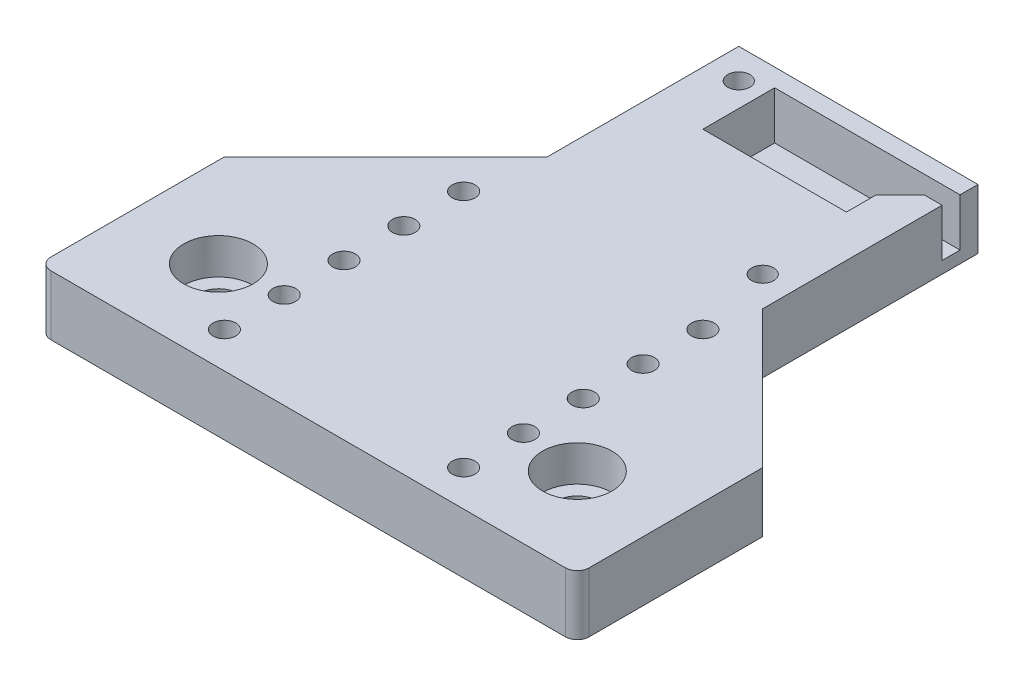
SolidWorks part; units mm, degrees
ref_plane "Front Plane" through (0, 0, 0) normal (0, 0, 1) x (1, 0, 0)
ref_plane "Top Plane" through (0, 0, 0) normal (0, 1, 0) x (1, 0, 0)
ref_plane "Right Plane" through (0, 0, 0) normal (1, 0, 0) x (0, 0, -1)
sketch "Sketch1" plane through (0, 0, 0) normal (0, 1, 0) x (1, 0, 0)
  line L0 (0, 0) -> (0, 22.5) construction
  line L1 (-22.5, -22.5) -> (22.5, -22.5)
  line L2 (-22.5, -22.5) -> (-22.5, 22.5)
  line L3 (-22.5, 22.5) -> (22.5, 22.5)
  line L4 (22.5, -22.5) -> (22.5, 22.5)
  line L5 (-22.5, -22.5) -> (22.5, 22.5) construction
  line L6 (-22.5, 22.5) -> (22.5, -22.5) construction
  line L7 (-15, 15) -> (-15, -15) construction
  line L8 (-15, 15) -> (15, 15) construction
  line L9 (0, 0) -> (-15, 0) construction
  circle A0 centre (-15, 15) radius 1.7
  circle A2 centre (-15, -15) radius 1.7
  circle A3 centre (15, -15) radius 1.7
  circle A5 centre (15, 15) radius 1.7
  point P0 (0, 0)
  dimension "D1" = 3.4
  dimension "D2" = 30
  dimension "D4" = 45
  dimension "D6" = 45
extrude "Boss-Extrude1" add sketch "Sketch1" along normal blind 5
sketch "Sketch7" plane through (0, 5, 0) normal (0, 1, 0) x (1, 0, 0)
  circle A0 centre (-15, 15) radius 2.9
  circle A1 centre (15, 15) radius 2.9
  circle A2 centre (-15, -15) radius 2.9
  circle A3 centre (15, -15) radius 2.9
  dimension "D1" = 5.8
extrude "Cut-Extrude6" cut sketch "Sketch7" against normal offset from surface (3 mm away) 2 up to face at (15, 0, 13.3)
sketch "Sketch4" plane through (0, 5, 0) normal (0, 1, 0) x (1, 0, 0)
  line L0 (11, 13.5) -> (0, 13.5) construction
  line L1 (-6.5, 7) -> (8.5, 7) construction
  line L2 (-6.5, 7) -> (-6.5, 20) construction
  line L3 (-6.5, 20) -> (8.5, 20) construction
  line L4 (8.5, 7) -> (8.5, 20) construction
  line L5 (-6.5, 7) -> (8.5, 20) construction
  line L6 (-6.5, 20) -> (8.5, 7) construction
  line L7 (-9, 4.5) -> (11, 4.5) construction
  line L8 (-9, 4.5) -> (-9, 22.5) construction
  line L9 (-9, 22.5) -> (11, 22.5) construction
  line L10 (11, 4.5) -> (11, 22.5) construction
  line L11 (-9, 4.5) -> (11, 22.5) construction
  line L12 (-9, 22.5) -> (11, 4.5) construction
  line L13 (0, 13.5) -> (0, 0) construction
  line L14 (22.5, 22.5) -> (-22.5, 22.5) construction
  circle A0 centre (-6.5, 20) radius 0.925
  circle A2 centre (8.5, 7) radius 0.925
  point P0 (1, 13.5)
  point P9 (1, 13.5)
  dimension "D1" = 1.85
  dimension "D2" = 15
  dimension "D3" = 13
  dimension "D4" = 20
  dimension "D5" = 18
  dimension "D6" = 11
extrude "Cut-Extrude3" cut sketch "Sketch4" against normal through all
sketch "Sketch5" plane through (0, 5, 0) normal (0, 1, 0) x (1, 0, 0)
  line L0 (0, 0) -> (0, -22.5) construction
  line L1 (-22.5, -22.5) -> (22.5, -22.5) construction
  circle A0 centre (-10, -19.5) radius 0.95
  circle A1 centre (10, -19.5) radius 0.95
  dimension "D3" = 1.9
  dimension "D1" = 20
  dimension "D2" = 3
extrude "Cut-Extrude4" cut sketch "Sketch5" against normal through all
pattern_linear "LPattern1" count 5 spacing 5 along (0, 0, -1) of "Cut-Extrude4"
fillet "Fillet1" radius 1 4 edges at (-22.5, 2.5, -22.5) (-22.5, 2.5, 22.5) (22.5, 2.5, 22.5) (22.5, 2.5, -22.5)
sketch "Sketch8" plane through (0, 5, 0) normal (0, 1, 0) x (1, 0, 0)
  line L1 (-4.5, 21) -> (7.5, 21)
  line L2 (-4.5, 21) -> (-4.5, 15)
  line L3 (-4.5, 15) -> (7.5, 15)
  line L4 (7.5, 21) -> (7.5, 15) construction
  line L6 (7.5, 21) -> (15.5, 21)
  line L7 (15.5, 21) -> (15.5, 19.5)
  line L8 (15.5, 19.5) -> (7.5, 19.5)
  line L9 (7.5, 19.5) -> (7.5, 15)
  line L10 (21.5, 22.5) -> (-21.5, 22.5) construction
  dimension "D1" = 4.5
  dimension "D2" = 7.5
  dimension "D3" = 6
  dimension "D4" = 8
  dimension "D5" = 1.5
  dimension "D7" = 1.5
extrude "Cut-Extrude7" cut sketch "Sketch8" against normal offset from surface (23.6186 mm away) 1
fillet "Fillet2" radius 3 1 edges at (15.5, 1, -20.25)
chamfer "Chamfer2" distance 2 angle 45 1 edges at (7.5, 3, -19.5)
sketch "Sketch9" plane through (0, 5, 0) normal (0, 1, 0) x (1, 0, 0)
  line L0 (-9, 22.5) -> (-9, 6.5)
  line L1 (21.5, 22.5) -> (-21.5, 22.5) construction
  line L2 (-9, 6.5) -> (-22.5, -7)
  line L3 (-22.5, 21.5) -> (-22.5, -21.5) construction
  line L4 (22.5, -21.5) -> (22.5, 21.5) construction
  line L5 (-22.5, 21.5) -> (-22.5, -7)
  line L6 (21.5, 22.5) -> (11, 22.5)
  line L7 (22.5, -7) -> (22.5, 21.5)
  line L8 (-22.5, -7) -> (22.5, -7) construction
  line L10 (11, 4.5) -> (22.5, -7)
  line L11 (11, 22.5) -> (11, 4.5)
  line L12 (-9, 22.5) -> (-21.5, 22.5)
  arc A0 (-21.5, 22.5) -> (-22.5, 21.5) centre (-21.5, 21.5) ccw construction
  arc A1 (22.5, 21.5) -> (21.5, 22.5) centre (21.5, 21.5) ccw construction
  arc A2 (-21.5, 22.5) -> (-22.5, 21.5) centre (-21.5, 21.5) ccw
  arc A3 (22.5, 21.5) -> (21.5, 22.5) centre (21.5, 21.5) ccw
  dimension "D1" = 11.5
  dimension "D2" = 45
  dimension "D3" = 13.5
  dimension "D4" = 45
  dimension "D5" = 18
extrude "Cut-Extrude8" cut sketch "Sketch9" against normal through all
